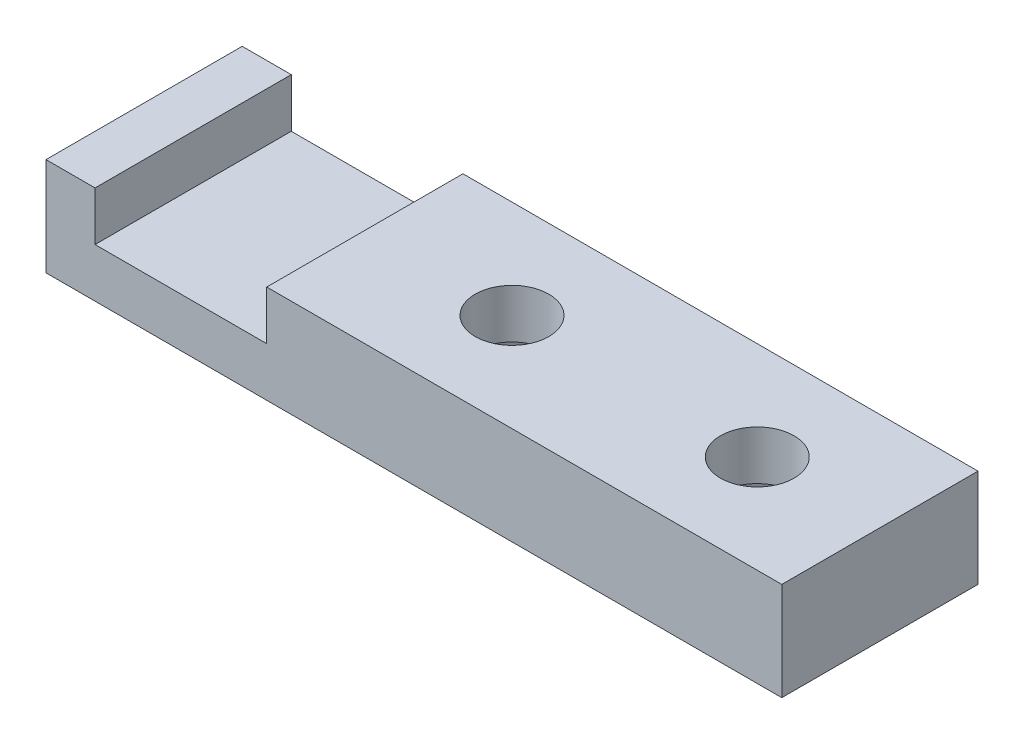
SolidWorks part; units mm, degrees
ref_plane "Front Plane" through (0, 0, 0) normal (0, 0, 1) x (1, 0, 0)
ref_plane "Top Plane" through (0, 0, 0) normal (0, 1, 0) x (1, 0, 0)
ref_plane "Right Plane" through (0, 0, 0) normal (1, 0, 0) x (0, 0, -1)
sketch "Sketch1" plane through (0, 0, 0) normal (0, 0, 1) x (1, 0, 0)
  line L1 (0, 0) -> (20, 0)
  line L2 (0, 0) -> (0, 4)
  line L3 (0, 4) -> (20, 4)
  line L4 (20, 0) -> (20, 4)
  dimension "D1" = 4
  dimension "D2" = 20
extrude "Boss-Extrude1" add sketch "Sketch1" along normal blind 8
sketch "Sketch2" plane through (0, 0, 8) normal (0, 0, 1) x (1, 0, 0)
  line L1 (20, 4) -> (0, 4) construction
  line L2 (2, 4) -> (9, 4)
  line L3 (2, 4) -> (2, 2)
  line L4 (2, 2) -> (9, 2)
  line L5 (9, 4) -> (9, 2)
  dimension "D1" = 7
  dimension "D2" = 2
extrude "Cut-Extrude1" cut sketch "Sketch2" against normal blind 8
sketch "Sketch3" plane through (20, 0, 0) normal (1, 0, 0) x (0, 0, -1)
  line L0 (-8, 4) -> (0, 4) construction
  line L1 (-8, 0) -> (0, 0)
  line L2 (-8, 0) -> (-8, 4)
  line L3 (-8, 4) -> (0, 4)
  line L4 (0, 0) -> (0, 4)
extrude "Boss-Extrude2" add sketch "Sketch3" along normal blind 10
sketch "Sketch4" plane through (0, 0, 0) normal (0, -1, 0) x (1, 0, 0)
  line L0 (30, 8) -> (30, 0) construction
  circle A0 centre (25, 4) radius 1.5
  circle A1 centre (15, 4) radius 1.5
  dimension "D2" = 3
  dimension "D4" = 3
  dimension "D1" = 5
  dimension "D3" = 10
extrude "Cut-Extrude2" cut sketch "Sketch4" against normal blind 10
sketch "Sketch5" plane through (0, 0, 0) normal (0, -1, 0) x (1, 0, 0)
  line L1 (22, 4) -> (23.5, 1.4019)
  line L2 (23.5, 1.4019) -> (26.5, 1.4019)
  line L3 (26.5, 1.4019) -> (28, 4)
  line L4 (28, 4) -> (26.5, 6.5981)
  line L5 (26.5, 6.5981) -> (23.5, 6.5981)
  line L6 (23.5, 6.5981) -> (22, 4)
  line L7 (12, 4) -> (13.5, 1.4019)
  line L8 (13.5, 1.4019) -> (16.5, 1.4019)
  line L9 (16.5, 1.4019) -> (18, 4)
  line L10 (18, 4) -> (16.5, 6.5981)
  line L11 (16.5, 6.5981) -> (13.5, 6.5981)
  line L12 (13.5, 6.5981) -> (12, 4)
  circle A0 centre (25, 4) radius 2.5981 construction
  circle A1 centre (15, 4) radius 2.5981 construction
  dimension "D1" = 3
  dimension "D2" = 3
extrude "Cut-Extrude3" cut sketch "Sketch5" against normal blind 2
